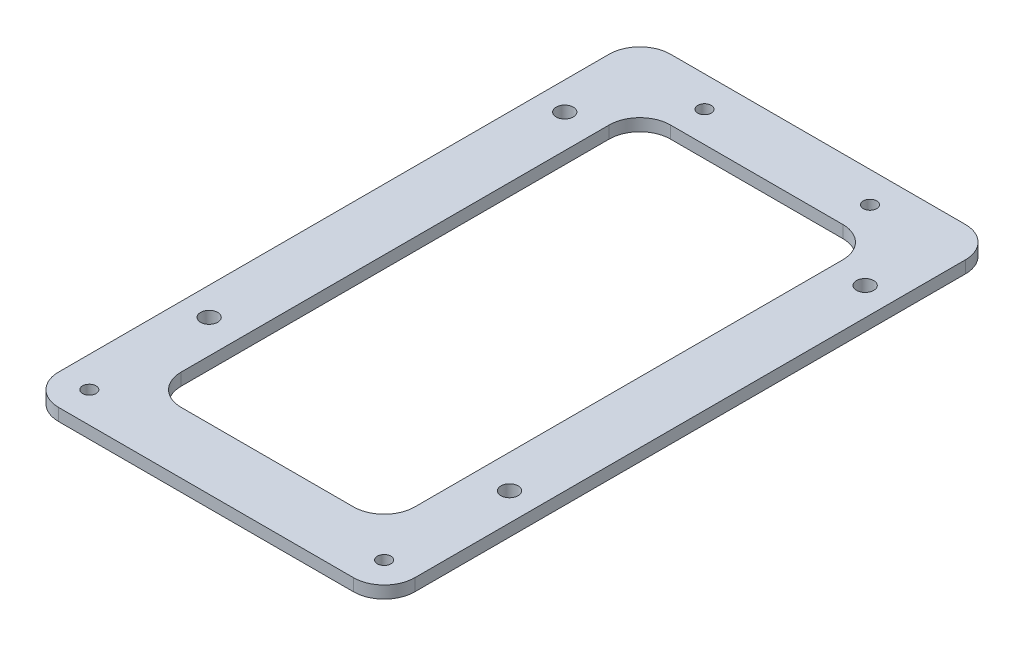
SolidWorks part; units mm, degrees
ref_plane "Front Plane" through (0, 0, 0) normal (0, 0, 1) x (1, 0, 0)
ref_plane "Top Plane" through (0, 0, 0) normal (0, 1, 0) x (1, 0, 0)
ref_plane "Right Plane" through (0, 0, 0) normal (1, 0, 0) x (0, 0, -1)
sketch "Sketch1" plane through (0, 0, 0) normal (0, 1, 0) x (1, 0, 0)
  line L8 (13, 13) -> (-13, 13)
  line L9 (13, -13) -> (13, 13)
  line L10 (-13, -13) -> (13, -13)
  line L11 (-13, 13) -> (-13, -13)
  circle A2 centre (13.5, 39.7) radius 0.95
  circle A4 centre (-13.5, 39.7) radius 0.95
  circle A6 centre (-24.05, -50.1) radius 0.95
  circle A8 centre (24.05, -50.1) radius 0.95
  circle A10 centre (-10.3, -10.3) radius 1.7
  circle A12 centre (10.3, 10.3) radius 1.7
  circle A14 centre (-10.3, 10.3) radius 1.7
  circle A16 centre (10.3, -10.3) radius 1.7
  dimension "D1" = 27
  dimension "D2" = 48.1
  dimension "D3" = 89.8
sketch "Sketch2" plane through (0, 0, 0) normal (0, 1, 0) x (1, 0, 0)
  line L0 (-29.05, 44.7) -> (-29.05, -55.1)
  line L1 (-24.05, 39.7) -> (24.05, 39.7) construction
  line L2 (-24.05, 39.7) -> (-24.05, -50.1) construction
  line L3 (-24.05, -50.1) -> (24.05, -50.1) construction
  line L4 (24.05, 39.7) -> (24.05, -50.1) construction
  line L5 (-29.05, -55.1) -> (29.05, -55.1)
  line L6 (29.05, 44.7) -> (29.05, -55.1)
  line L7 (-29.05, 44.7) -> (29.05, 44.7)
  line L8 (-19.05, 34.7) -> (-19.05, -45.1)
  line L9 (-19.05, -45.1) -> (19.05, -45.1)
  line L10 (19.05, 34.7) -> (19.05, -45.1)
  line L11 (-19.05, 34.7) -> (19.05, 34.7)
  line L12 (24.05, 24.05) -> (-24.05, -24.05) construction
  line L13 (-24.05, 24.05) -> (24.05, -24.05) construction
  line L15 (-24.5, 27.9) -> (24.5, 27.9) construction
  line L16 (-24.5, 27.9) -> (-24.5, -30.1) construction
  line L17 (-24.5, -30.1) -> (24.5, -30.1) construction
  line L18 (24.5, 27.9) -> (24.5, -30.1) construction
  circle A0 centre (-24.05, -50.1) radius 1.1
  circle A1 centre (24.05, -50.1) radius 1.1
  circle A2 centre (-13.5, 39.7) radius 1.1
  circle A3 centre (13.5, 39.7) radius 1.1
  circle A4 centre (-10.3, 10.3) radius 0.95
  circle A5 centre (-10.3, -10.3) radius 0.95
  circle A6 centre (10.3, -10.3) radius 0.95
  circle A7 centre (10.3, 10.3) radius 0.95
  circle A8 centre (24.05, -50.1) radius 0.95 construction
  circle A9 centre (24.5, 27.9) radius 1.4
  circle A10 centre (-24.5, 27.9) radius 1.4
  circle A11 centre (24.5, -30.1) radius 1.4
  circle A12 centre (-24.5, -30.1) radius 1.4
  point P44 (0, 27.9)
  dimension "D3" = 2.2
  dimension "D7" = 2.8
  dimension "D4" = 49
  dimension "D5" = 58
  dimension "D6" = 25
  dimension "D1" = 5
  dimension "D2" = 5
sketch "Sketch3" plane through (0, 0, 0) normal (0, 1, 0) x (1, 0, 0)
  line L0 (-24.05, 24.05) -> (24.05, -24.05) construction
  line L1 (24.05, 24.05) -> (-24.05, -24.05) construction
  line L2 (-24.05, 24.05) -> (24.05, -24.05) construction
  line L3 (24.05, 24.05) -> (-24.05, -24.05) construction
  line L4 (-29.05, 44.7) -> (-29.05, -55.1)
  line L5 (-29.05, -55.1) -> (29.05, -55.1)
  line L6 (29.05, -55.1) -> (29.05, 44.7)
  line L7 (29.05, 44.7) -> (-29.05, 44.7)
  line L8 (-29.05, 44.7) -> (-29.05, -55.1)
  line L9 (-29.05, -55.1) -> (29.05, -55.1)
  line L10 (29.05, -55.1) -> (29.05, 44.7)
  line L11 (29.05, 44.7) -> (-29.05, 44.7)
  line L12 (19.05, -45.1) -> (19.05, 34.7)
  line L13 (-19.05, -45.1) -> (19.05, -45.1)
  line L14 (-19.05, 34.7) -> (-19.05, -45.1)
  line L15 (19.05, 34.7) -> (-19.05, 34.7)
  line L16 (19.05, -45.1) -> (19.05, -22.0906)
  line L17 (-19.05, -45.1) -> (19.05, -45.1)
  line L18 (-19.05, 34.7) -> (-19.05, 22.0906)
  line L19 (19.05, 34.7) -> (-19.05, 34.7)
  line L20 (19.05, 22.0906) -> (8.7797, 11.8203)
  line L21 (-19.05, 16.0094) -> (-11.8203, 8.7797)
  line L22 (19.05, 16.0094) -> (11.8203, 8.7797)
  line L23 (-19.05, 22.0906) -> (-8.7797, 11.8203)
  line L24 (11.8203, -8.7797) -> (19.05, -16.0094)
  line L25 (-22.5297, 25.5703) -> (25.5703, -22.5297) construction
  line L26 (-11.8203, -8.7797) -> (-19.05, -16.0094)
  line L27 (22.5297, 25.5703) -> (-25.5703, -22.5297) construction
  line L28 (-8.7797, -11.8203) -> (-19.05, -22.0906)
  line L29 (25.5703, 22.5297) -> (-22.5297, -25.5703) construction
  line L30 (-19.05, 16.0094) -> (-19.05, -16.0094)
  line L31 (-25.5703, 22.5297) -> (22.5297, -25.5703) construction
  line L32 (8.7797, -11.8203) -> (19.05, -22.0906)
  line L33 (-19.05, -22.0906) -> (-19.05, -45.1)
  line L34 (19.05, -16.0094) -> (19.05, 16.0094)
  line L35 (19.05, 22.0906) -> (19.05, 34.7)
  arc A0 (8.7797, 11.8203) -> (11.8203, 8.7797) centre (10.3, 10.3) ccw
  circle A1 centre (24.05, -50.1) radius 1.1
  circle A2 centre (24.05, -50.1) radius 1.1
  circle A3 centre (-10.3, -10.3) radius 0.95
  circle A4 centre (-10.3, -10.3) radius 0.95
  circle A5 centre (13.5, 39.7) radius 1.1
  circle A6 centre (13.5, 39.7) radius 1.1
  circle A7 centre (-13.5, 39.7) radius 1.1
  circle A8 centre (-13.5, 39.7) radius 1.1
  circle A9 centre (-24.05, -50.1) radius 1.1
  circle A10 centre (-24.05, -50.1) radius 1.1
  circle A11 centre (-24.5, 27.9) radius 1.4
  circle A12 centre (-24.5, 27.9) radius 1.4
  circle A13 centre (24.5, 27.9) radius 1.4
  circle A14 centre (24.5, 27.9) radius 1.4
  circle A15 centre (10.3, 10.3) radius 0.95
  circle A16 centre (10.3, 10.3) radius 0.95
  circle A17 centre (10.3, -10.3) radius 0.95
  circle A18 centre (10.3, -10.3) radius 0.95
  circle A19 centre (-10.3, 10.3) radius 0.95
  circle A20 centre (-10.3, 10.3) radius 0.95
  circle A21 centre (-24.5, -30.1) radius 1.4
  circle A22 centre (-24.5, -30.1) radius 1.4
  circle A23 centre (24.5, -30.1) radius 1.4
  circle A24 centre (24.5, -30.1) radius 1.4
  arc A25 (11.8203, -8.7797) -> (8.7797, -11.8203) centre (10.3, -10.3) ccw
  arc A26 (-8.7797, -11.8203) -> (-11.8203, -8.7797) centre (-10.3, -10.3) ccw
  arc A27 (-11.8203, 8.7797) -> (-8.7797, 11.8203) centre (-10.3, 10.3) ccw
  dimension "D17" = 2.15
  dimension "D1" = 0
  dimension "D2" = 0
  dimension "D3" = 0
  dimension "D4" = 0
  dimension "D5" = 0
  dimension "D6" = 0
  dimension "D7" = 0
  dimension "D8" = 0
  dimension "D9" = 0
  dimension "D10" = 0
  dimension "D11" = 0
  dimension "D12" = 0
  dimension "D13" = 0
  dimension "D14" = 0
  dimension "D15" = 2.15
  dimension "D16" = 2.15
extrude "Boss-Extrude1" add sketch "Sketch3" along normal blind 2
fillet "Fillet1" radius 5 8 edges at (19.05, 1, 45.1) (-19.05, 1, 45.1) (19.05, 1, -34.7) (-29.05, 1, -44.7) (-19.05, 1, -34.7) (29.05, 1, -44.7) (29.05, 1, 55.1) (-29.05, 1, 55.1)
fillet "Fillet2" radius 3 4 edges at (-19.05, 1, 16.0094) (-19.05, 1, -16.0094) (19.05, 1, -16.0094) (19.05, 1, 16.0094)
fillet "Fillet3" radius 10 4 edges at (-19.05, 1, -22.0906) (-19.05, 1, 22.0906) (19.05, 1, -22.0906) (19.05, 1, 22.0906)
sketch "Sketch4" plane through (0, 0, 0) normal (0, -1, 0) x (1, 0, 0)
  circle A0 centre (-10.3, 10.3) radius 1.6
  circle A1 centre (10.3, 10.3) radius 1.6
  circle A2 centre (10.3, -10.3) radius 1.6
  circle A3 centre (-10.3, -10.3) radius 1.6
  circle A4 centre (-10.3, -10.3) radius 0.95 construction
  circle A5 centre (10.3, -10.3) radius 0.95 construction
  circle A6 centre (10.3, 10.3) radius 0.95 construction
  circle A7 centre (-10.3, 10.3) radius 0.95 construction
  circle A8 centre (-10.3, -10.3) radius 0.95
  circle A9 centre (10.3, -10.3) radius 0.95
  circle A10 centre (10.3, 10.3) radius 0.95
  circle A11 centre (-10.3, 10.3) radius 0.95
  dimension "D1" = 3.2
extrude "Boss-Extrude2" add sketch "Sketch4" along normal blind 1
sketch "Sketch5" plane through (0, 2, 0) normal (0, 1, 0) x (1, 0, 0)
  line L0 (-19.05, 29.7) -> (-19.05, 26.2327) construction
  line L1 (-19.05, 27.9663) -> (19.05, 27.9663)
  line L2 (-19.05, 27.9663) -> (-19.05, -33.1663)
  line L3 (-19.05, -33.1663) -> (19.05, -33.1663)
  line L4 (19.05, 27.9663) -> (19.05, -33.1663)
  line L5 (19.05, -40.1) -> (19.05, -26.2327) construction
extrude "Cut-Extrude1" cut sketch "Sketch5" against normal through all
